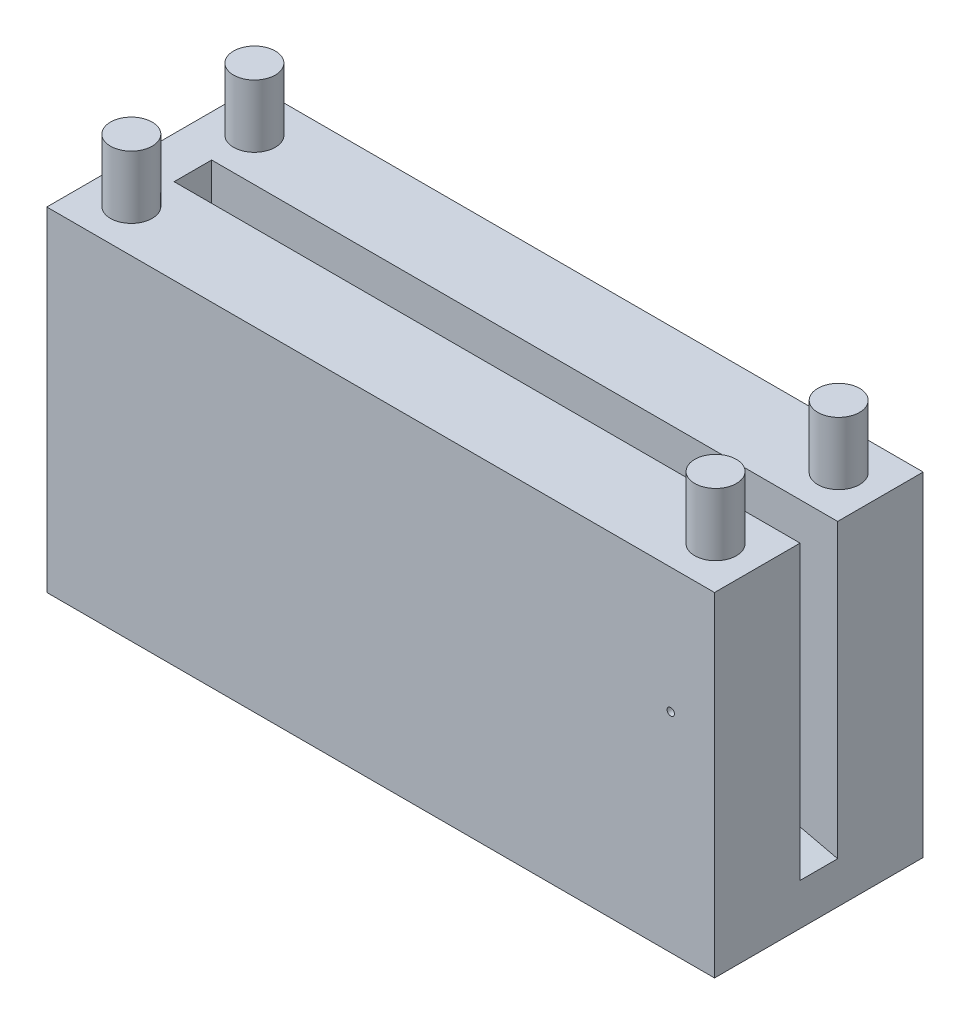
SolidWorks part; units mm, degrees
ref_plane "Front Plane" through (0, 0, 0) normal (0, 0, 1) x (1, 0, 0)
ref_plane "Top Plane" through (0, 0, 0) normal (0, 1, 0) x (1, 0, 0)
ref_plane "Right Plane" through (0, 0, 0) normal (1, 0, 0) x (0, 0, -1)
sketch "Sketch1" plane through (0, 0, 0) normal (0, 1, 0) x (1, 0, 0)
  line L1 (-101.6, 31.75) -> (101.6, 31.75)
  line L2 (-101.6, 31.75) -> (-101.6, -31.75)
  line L3 (-101.6, -31.75) -> (101.6, -31.75)
  line L4 (101.6, 31.75) -> (101.6, -31.75)
  line L5 (-101.6, 31.75) -> (101.6, -31.75) construction
  line L6 (-101.6, -31.75) -> (101.6, 31.75) construction
  point P0 (0, 0)
  dimension "D1" = 203.2
  dimension "D2" = 63.5
extrude "Boss-Extrude1" add sketch "Sketch1" along normal blind 101.6
sketch "Sketch3" plane through (0, 101.6, 0) normal (0, 1, 0) x (1, 0, 0)
  line L0 (101.6, 5.715) -> (101.6, -5.715)
  line L1 (101.6, 5.715) -> (-88.9, 5.715)
  line L2 (101.6, -5.715) -> (-88.9, -5.715)
  line L3 (-88.9, 5.715) -> (-88.9, -5.715)
  line L4 (101.6, -31.75) -> (101.6, 31.75) construction
  line L5 (-101.6, 31.75) -> (-101.6, -31.75) construction
  line L7 (101.6, 5.715) -> (101.6, 31.75) construction
  line L8 (101.6, -5.715) -> (101.6, -31.75) construction
  dimension "D1" = 12.7
  dimension "D2" = 11.43
extrude "Cut-Extrude1" cut sketch "Sketch3" against normal blind 6.35
sketch "Sketch4" plane through (0, 0, -5.715) normal (0, 0, 1) x (1, 0, 0)
  line L0 (-88.9, 101.6) -> (-88.9, 57.15)
  line L3 (-101.6, 101.6) -> (101.6, 101.6) construction
  line L4 (-88.9, 57.15) -> (101.6, 12.7)
  line L5 (101.6, 101.6) -> (101.6, 0) construction
  line L6 (-101.6, 0) -> (101.6, 0) construction
  line L7 (-88.9, 101.6) -> (101.6, 101.6)
  line L8 (101.6, 101.6) -> (101.6, 12.7)
  dimension "D1" = 44.45
  dimension "D2" = 12.7
extrude "Cut-Extrude2" cut sketch "Sketch4" along normal up to surface (11.43 mm away) up to face at (6.35, 98.425, 5.715)
sketch "Sketch5" plane through (0, 101.6, 0) normal (0, 1, 0) x (1, 0, 0)
  line L1 (-101.6, 31.75) -> (-101.6, -31.75) construction
  line L3 (101.6, -31.75) -> (101.6, -5.715) construction
  line L4 (88.9, -18.7325) -> (88.9, -31.75) construction
  line L5 (-101.6, -31.75) -> (101.6, -31.75) construction
  line L6 (88.9, -18.7325) -> (88.9, -5.715) construction
  line L7 (-88.9, -5.715) -> (101.6, -5.715) construction
  line L8 (88.9, -18.7325) -> (88.9, 18.7325) construction
  circle A1 centre (88.9, -18.7325) radius 6.35
  circle A2 centre (-88.9, -18.7325) radius 6.35
  circle A3 centre (-88.9, 18.7325) radius 6.35
  circle A4 centre (88.9, 18.7325) radius 6.35
  dimension "D1" = 6.35
  dimension "D2" = 12.7
  dimension "D3" = 2
  dimension "D6" = 6.35
  dimension "D5" = 37.465
  dimension "D4" = 2
extrude "Boss-Extrude2" add sketch "Sketch5" along normal blind 19.05
sketch "Sketch6" plane through (0, 0, -5.715) normal (0, 0, 1) x (1, 0, 0)
  line L0 (101.6, 101.6) -> (-88.9, 101.6) construction
  line L1 (101.6, 12.7) -> (101.6, 101.6) construction
  circle A0 centre (88.265, 63.5) radius 1.125
  dimension "D1" = 2.25
  dimension "D2" = 38.1
  dimension "D3" = 13.335
extrude "Cut-Extrude3" cut sketch "Sketch6" against normal through all both and the other way through all
